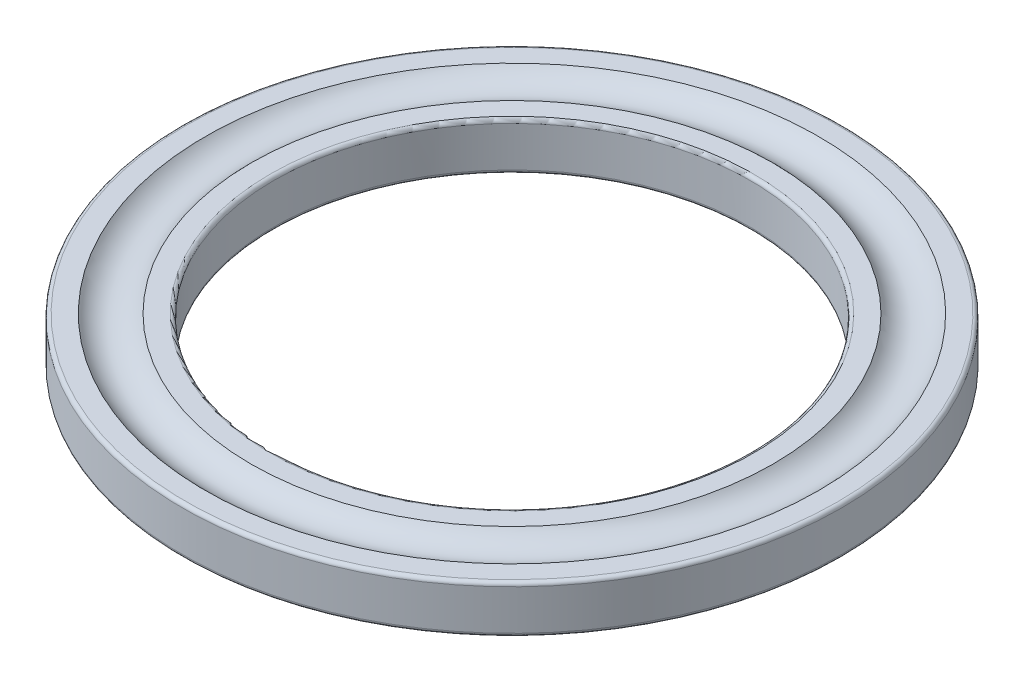
SolidWorks part; units mm, degrees
material "AISI Type 316L stainless steel"
ref_plane "Front Plane" through (0, 0, 0) normal (0, 0, 1) x (1, 0, 0)
ref_plane "Top Plane" through (0, 0, 0) normal (0, 1, 0) x (1, 0, 0)
ref_plane "Right Plane" through (0, 0, 0) normal (1, 0, 0) x (0, 0, -1)
sketch "Sketch1" plane through (0, 0, 0) normal (0, 0, 1) x (1, 0, 0)
  line L0 (0, 0) -> (32.5, 0) construction
  line L1 (32.5, 0) -> (45, 0)
  line L2 (45, 0) -> (45, 6.5)
  line L3 (45, 6.5) -> (41.8725, 6.5)
  line L5 (35.6275, 6.5) -> (32.5, 6.5)
  line L6 (32.5, 6.5) -> (32.5, 0)
  line L7 (0, 0) -> (0, 18) construction
  line L8 (38.75, 0) -> (38.75, 9) construction
  line L9 (32.5, 11.5) -> (32.5, 18) construction
  line L10 (32.5, 18) -> (45, 18) construction
  line L11 (45, 18) -> (45, 11.5) construction
  line L12 (45, 11.5) -> (41.8725, 11.5) construction
  line L13 (38.75, 9) -> (38.75, 18) construction
  line L14 (35.6275, 11.5) -> (32.5, 11.5) construction
  arc A1 (35.6275, 6.5) -> (41.8725, 6.5) centre (38.75, 9) ccw
  arc A2 (41.8725, 11.5) -> (35.6275, 11.5) centre (38.75, 9) ccw construction
  point P9 (0, 9)
  dimension "D2" = 18
  dimension "D6" = 8
  dimension "D1" = 5
  dimension "D3" = 32.5
  dimension "D4" = 45
  dimension "D5" = 6.5
  dimension "D7" = 38.75
revolve "Revolve1" add sketch "Sketch1" angle 360 about L7
fillet "Fillet1" radius 0.5 4 edges at (32.5, 0, 0) (45, 0, 0) (45, 6.5, 0) (32.5, 6.5, 0)
